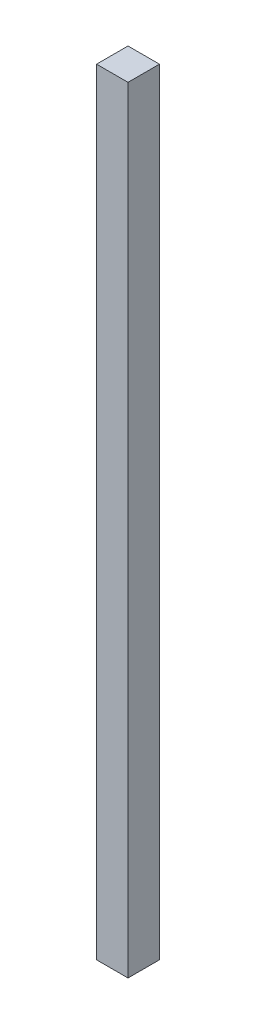
SolidWorks part; units mm, degrees
ref_plane "Front Plane" through (0, 0, 0) normal (0, 0, 1) x (1, 0, 0)
ref_plane "Top Plane" through (0, 0, 0) normal (0, 1, 0) x (1, 0, 0)
ref_plane "Right Plane" through (0, 0, 0) normal (1, 0, 0) x (0, 0, -1)
sketch "Sketch1" plane through (0, 0, 0) normal (0, 1, 0) x (1, 0, 0)
  line L1 (0, 0) -> (15, 0)
  line L2 (0, 0) -> (0, 15)
  line L3 (0, 15) -> (15, 15)
  line L4 (15, 0) -> (15, 15)
  dimension "D1" = 15
  dimension "D2" = 15
extrude "Boss-Extrude1" add sketch "Sketch1" along normal blind 370 contours L3 L4 L1 L2
